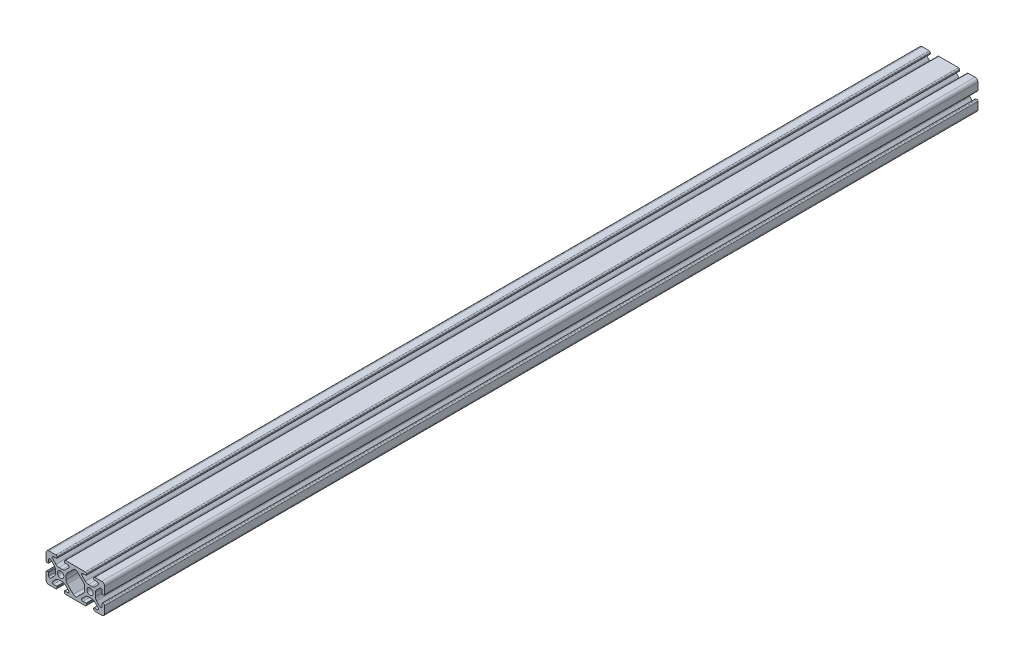
SolidWorks part; units mm, degrees
ref_plane "Plan de face" through (0, 0, 0) normal (0, 0, 1) x (1, 0, 0)
ref_plane "Plan de dessus" through (0, 0, 0) normal (0, 1, 0) x (1, 0, 0)
ref_plane "Plan de droite" through (0, 0, 0) normal (1, 0, 0) x (0, 0, -1)
ref_plane "Plan1" through (0, 0, 0) normal (0, 0, -1) x (-1, 0, 0)
sketch "Esquisse1" plane through (0, 0, 0) normal (0, 0, -1) x (-1, 0, 0)
  line L0 (-40, 6.7) -> (-40, 2)
  line L1 (-38, 0) -> (-33.3, 0)
  line L2 (-32.5, 0.8) -> (-32.5, 1.5)
  line L3 (-32.8, 1.8) -> (-34.9184, 1.8)
  line L4 (-35.5064, 3.2196) -> (-33.2547, 5.4713)
  line L5 (-31.1334, 6.35) -> (-28.8666, 6.35)
  line L6 (-26.7453, 5.4713) -> (-24.4936, 3.2196)
  line L7 (-25.0816, 1.8) -> (-27.2, 1.8)
  line L8 (-27.5, 1.5) -> (-27.5, 0.8)
  line L9 (-26.7, 0) -> (-13.3, 0)
  line L10 (-12.5, 0.8) -> (-12.5, 1.5)
  line L11 (-12.8, 1.8) -> (-14.9184, 1.8)
  line L12 (-15.5064, 3.2196) -> (-13.2547, 5.4713)
  line L13 (-11.1334, 6.35) -> (-8.8666, 6.35)
  line L14 (-6.7453, 5.4713) -> (-4.4936, 3.2196)
  line L15 (-5.0816, 1.8) -> (-7.2, 1.8)
  line L16 (-7.5, 1.5) -> (-7.5, 0.8)
  line L17 (-6.7, 0) -> (-2, 0)
  line L18 (0, 2) -> (0, 6.7)
  line L19 (-0.8, 7.5) -> (-1.5, 7.5)
  line L20 (-1.8, 7.2) -> (-1.8, 5.0816)
  line L21 (-3.2196, 4.4936) -> (-5.4713, 6.7453)
  line L22 (-6.35, 8.8666) -> (-6.35, 11.1334)
  line L23 (-5.4713, 13.2547) -> (-3.2196, 15.5064)
  line L24 (-1.8, 14.9184) -> (-1.8, 12.8)
  line L25 (-1.5, 12.5) -> (-0.8, 12.5)
  line L26 (0, 13.3) -> (0, 18)
  line L27 (-2, 20) -> (-6.7, 20)
  line L28 (-7.5, 19.2) -> (-7.5, 18.5)
  line L29 (-7.2, 18.2) -> (-5.0816, 18.2)
  line L30 (-4.4936, 16.7804) -> (-6.7453, 14.5287)
  line L31 (-8.8666, 13.65) -> (-11.1334, 13.65)
  line L32 (-13.2547, 14.5287) -> (-15.5064, 16.7804)
  line L33 (-14.9184, 18.2) -> (-12.8, 18.2)
  line L34 (-12.5, 18.5) -> (-12.5, 19.2)
  line L35 (-13.3, 20) -> (-26.7, 20)
  line L36 (-27.5, 19.2) -> (-27.5, 18.5)
  line L37 (-27.2, 18.2) -> (-25.0816, 18.2)
  line L38 (-24.4936, 16.7804) -> (-26.7453, 14.5287)
  line L39 (-28.8666, 13.65) -> (-31.1334, 13.65)
  line L40 (-33.2547, 14.5287) -> (-35.5064, 16.7804)
  line L41 (-34.9184, 18.2) -> (-32.8, 18.2)
  line L42 (-32.5, 18.5) -> (-32.5, 19.2)
  line L43 (-33.3, 20) -> (-38, 20)
  line L44 (-40, 18) -> (-40, 13.3)
  line L45 (-39.2, 12.5) -> (-38.5, 12.5)
  line L46 (-38.2, 12.8) -> (-38.2, 14.9184)
  line L47 (-36.7804, 15.5064) -> (-34.5287, 13.2547)
  line L48 (-33.65, 11.1334) -> (-33.65, 8.8666)
  line L49 (-34.5287, 6.7453) -> (-36.7804, 4.4936)
  line L50 (-38.2, 5.0816) -> (-38.2, 7.2)
  line L51 (-38.5, 7.5) -> (-39.2, 7.5)
  line L52 (-18.5858, 17.313) -> (-14.5287, 13.2559)
  line L53 (-13.65, 11.1346) -> (-13.65, 8.8654)
  line L54 (-14.5287, 6.7441) -> (-18.5858, 2.687)
  line L55 (-21.4142, 2.687) -> (-25.4713, 6.7441)
  line L56 (-26.35, 8.8654) -> (-26.35, 11.1346)
  line L57 (-25.4713, 13.2559) -> (-21.4142, 17.313)
  arc A0 (-39.2, 7.5) -> (-40, 6.7) centre (-39.2, 6.7) ccw
  arc A1 (-40, 2) -> (-38, 0) centre (-38, 2) ccw
  arc A2 (-33.3, 0) -> (-32.5, 0.8) centre (-33.3, 0.8) ccw
  arc A3 (-32.5, 1.5) -> (-32.8, 1.8) centre (-32.8, 1.5) ccw
  arc A4 (-34.9184, 1.8) -> (-35.5064, 3.2196) centre (-34.9184, 2.6316) cw
  arc A5 (-33.2547, 5.4713) -> (-31.1334, 6.35) centre (-31.1334, 3.35) cw
  arc A6 (-28.8666, 6.35) -> (-26.7453, 5.4713) centre (-28.8666, 3.35) cw
  arc A7 (-24.4936, 3.2196) -> (-25.0816, 1.8) centre (-25.0816, 2.6316) cw
  arc A8 (-27.2, 1.8) -> (-27.5, 1.5) centre (-27.2, 1.5) ccw
  arc A9 (-27.5, 0.8) -> (-26.7, 0) centre (-26.7, 0.8) ccw
  arc A10 (-13.3, 0) -> (-12.5, 0.8) centre (-13.3, 0.8) ccw
  arc A11 (-12.5, 1.5) -> (-12.8, 1.8) centre (-12.8, 1.5) ccw
  arc A12 (-14.9184, 1.8) -> (-15.5064, 3.2196) centre (-14.9184, 2.6316) cw
  arc A13 (-13.2547, 5.4713) -> (-11.1334, 6.35) centre (-11.1334, 3.35) cw
  arc A14 (-8.8666, 6.35) -> (-6.7453, 5.4713) centre (-8.8666, 3.35) cw
  arc A15 (-4.4936, 3.2196) -> (-5.0816, 1.8) centre (-5.0816, 2.6316) cw
  arc A16 (-7.2, 1.8) -> (-7.5, 1.5) centre (-7.2, 1.5) ccw
  arc A17 (-7.5, 0.8) -> (-6.7, 0) centre (-6.7, 0.8) ccw
  arc A18 (-2, 0) -> (0, 2) centre (-2, 2) ccw
  arc A19 (0, 6.7) -> (-0.8, 7.5) centre (-0.8, 6.7) ccw
  arc A20 (-1.5, 7.5) -> (-1.8, 7.2) centre (-1.5, 7.2) ccw
  arc A21 (-1.8, 5.0816) -> (-3.2196, 4.4936) centre (-2.6316, 5.0816) cw
  arc A22 (-5.4713, 6.7453) -> (-6.35, 8.8666) centre (-3.35, 8.8666) cw
  arc A23 (-6.35, 11.1334) -> (-5.4713, 13.2547) centre (-3.35, 11.1334) cw
  arc A24 (-3.2196, 15.5064) -> (-1.8, 14.9184) centre (-2.6316, 14.9184) cw
  arc A25 (-1.8, 12.8) -> (-1.5, 12.5) centre (-1.5, 12.8) ccw
  arc A26 (-0.8, 12.5) -> (0, 13.3) centre (-0.8, 13.3) ccw
  arc A27 (0, 18) -> (-2, 20) centre (-2, 18) ccw
  arc A28 (-6.7, 20) -> (-7.5, 19.2) centre (-6.7, 19.2) ccw
  arc A29 (-7.5, 18.5) -> (-7.2, 18.2) centre (-7.2, 18.5) ccw
  arc A30 (-5.0816, 18.2) -> (-4.4936, 16.7804) centre (-5.0816, 17.3684) cw
  arc A31 (-6.7453, 14.5287) -> (-8.8666, 13.65) centre (-8.8666, 16.65) cw
  arc A32 (-11.1334, 13.65) -> (-13.2547, 14.5287) centre (-11.1334, 16.65) cw
  arc A33 (-15.5064, 16.7804) -> (-14.9184, 18.2) centre (-14.9184, 17.3684) cw
  arc A34 (-12.8, 18.2) -> (-12.5, 18.5) centre (-12.8, 18.5) ccw
  arc A35 (-12.5, 19.2) -> (-13.3, 20) centre (-13.3, 19.2) ccw
  arc A36 (-26.7, 20) -> (-27.5, 19.2) centre (-26.7, 19.2) ccw
  arc A37 (-27.5, 18.5) -> (-27.2, 18.2) centre (-27.2, 18.5) ccw
  arc A38 (-25.0816, 18.2) -> (-24.4936, 16.7804) centre (-25.0816, 17.3684) cw
  arc A39 (-26.7453, 14.5287) -> (-28.8666, 13.65) centre (-28.8666, 16.65) cw
  arc A40 (-31.1334, 13.65) -> (-33.2547, 14.5287) centre (-31.1334, 16.65) cw
  arc A41 (-35.5064, 16.7804) -> (-34.9184, 18.2) centre (-34.9184, 17.3684) cw
  arc A42 (-32.8, 18.2) -> (-32.5, 18.5) centre (-32.8, 18.5) ccw
  arc A43 (-32.5, 19.2) -> (-33.3, 20) centre (-33.3, 19.2) ccw
  arc A44 (-38, 20) -> (-40, 18) centre (-38, 18) ccw
  arc A45 (-40, 13.3) -> (-39.2, 12.5) centre (-39.2, 13.3) ccw
  arc A46 (-38.5, 12.5) -> (-38.2, 12.8) centre (-38.5, 12.8) ccw
  arc A47 (-38.2, 14.9184) -> (-36.7804, 15.5064) centre (-37.3684, 14.9184) cw
  arc A48 (-34.5287, 13.2547) -> (-33.65, 11.1334) centre (-36.65, 11.1334) cw
  arc A49 (-33.65, 8.8666) -> (-34.5287, 6.7453) centre (-36.65, 8.8666) cw
  arc A50 (-36.7804, 4.4936) -> (-38.2, 5.0816) centre (-37.3684, 5.0816) cw
  arc A51 (-38.2, 7.2) -> (-38.5, 7.5) centre (-38.5, 7.2) ccw
  circle A52 centre (-10, 10) radius 2.15
  circle A53 centre (-30, 10) radius 2.15
  arc A54 (-21.4142, 17.313) -> (-18.5858, 17.313) centre (-20, 15.8988) cw
  arc A55 (-14.5287, 13.2559) -> (-13.65, 11.1346) centre (-16.65, 11.1346) cw
  arc A56 (-13.65, 8.8654) -> (-14.5287, 6.7441) centre (-16.65, 8.8654) cw
  arc A57 (-18.5858, 2.687) -> (-21.4142, 2.687) centre (-20, 4.1012) cw
  arc A58 (-25.4713, 6.7441) -> (-26.35, 8.8654) centre (-23.35, 8.8654) cw
  arc A59 (-26.35, 11.1346) -> (-25.4713, 13.2559) centre (-23.35, 11.1346) cw
extrude "Boss.-Extru.1" add sketch "Esquisse1" against normal mid plane 595
